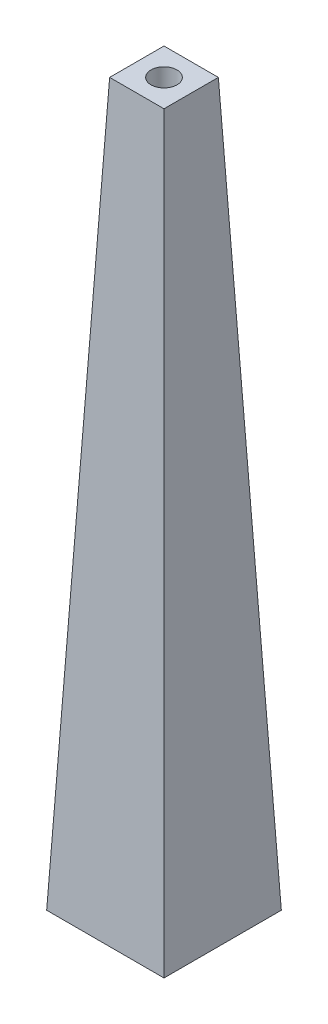
SolidWorks part; units mm, degrees
ref_plane "Front Plane" through (0, 0, 0) normal (0, 0, 1) x (1, 0, 0)
ref_plane "Top Plane" through (0, 0, 0) normal (0, 1, 0) x (1, 0, 0)
ref_plane "Right Plane" through (0, 0, 0) normal (1, 0, 0) x (0, 0, -1)
sketch "Sketch1" plane through (0, 0, 0) normal (0, 1, 0) x (1, 0, 0)
  line L1 (0, 0) -> (47.625, 0)
  line L2 (0, 0) -> (0, -47.625)
  line L3 (0, -47.625) -> (47.625, -47.625)
  line L4 (47.625, 0) -> (47.625, -47.625)
  dimension "D1" = 47.625
  dimension "D2" = 47.625
  dimension "D3" = 0
  dimension "D4" = 0
extrude "Boss-Extrude1" add sketch "Sketch1" along normal blind 381 draft 2.5
sketch "Sketch2" plane through (0, 0, 0) normal (0, -1, 0) x (1, 0, 0)
  line L0 (0, 23.8125) -> (47.625, 23.8125) construction
  line L1 (0, 0) -> (0, 47.625) construction
  line L2 (47.625, 47.625) -> (47.625, 0) construction
  line L3 (23.8125, 47.625) -> (23.8125, 0) construction
  line L4 (0, 47.625) -> (47.625, 47.625) construction
  line L5 (47.625, 0) -> (0, 0) construction
  circle A0 centre (23.8125, 23.8125) radius 3.429
  dimension "D1" = 6.858
extrude "Cut-Extrude1" cut sketch "Sketch2" against normal blind 381
sketch "Sketch3" plane through (0, 0, 0) normal (0, -1, 0) x (1, 0, 0)
  line L1 (0, 47.625) -> (47.625, 47.625)
  line L2 (0, 47.625) -> (0, 0)
  line L3 (0, 0) -> (47.625, 0)
  line L4 (47.625, 47.625) -> (47.625, 0)
extrude "Cut-Extrude2" cut sketch "Sketch3" against normal blind 190.5
sketch "Sketch4" plane through (0, 190.5, 0) normal (0, -1, 0) x (1, 0, 0)
  line L0 (23.8125, 39.3076) -> (23.8125, 8.3174) construction
  line L1 (39.3076, 39.3076) -> (8.3174, 39.3076) construction
  line L2 (8.3174, 8.3174) -> (39.3076, 8.3174) construction
  line L3 (39.3076, 23.8125) -> (8.3174, 23.8125) construction
  line L4 (39.3076, 8.3174) -> (39.3076, 39.3076) construction
  line L5 (8.3174, 39.3076) -> (8.3174, 8.3174) construction
  line L7 (15.875, 31.75) -> (31.75, 31.75)
  line L8 (15.875, 31.75) -> (15.875, 15.875)
  line L9 (15.875, 15.875) -> (31.75, 15.875)
  line L10 (31.75, 31.75) -> (31.75, 15.875)
  dimension "D1" = 15.875
  dimension "D2" = 15.875
  dimension "D3" = 7.9375
  dimension "D4" = 7.9375
extrude "Cut-Extrude3" cut sketch "Sketch4" against normal blind 6.985 draft 30
